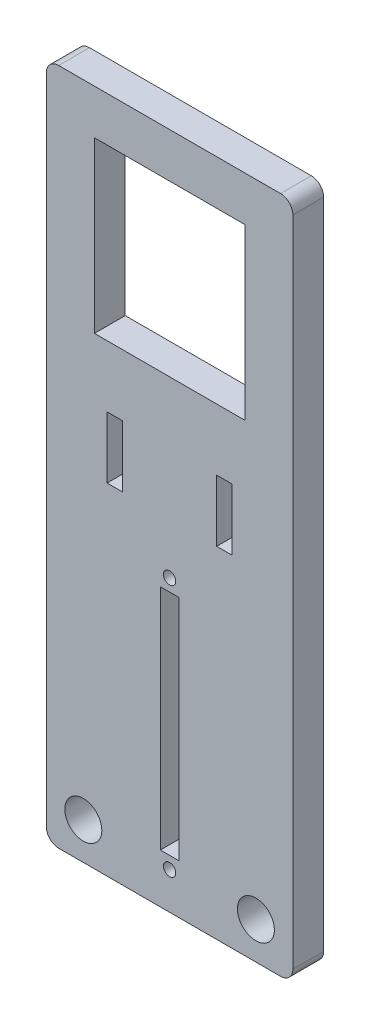
SolidWorks part; units mm, degrees
ref_plane "Front Plane" through (0, 0, 0) normal (0, 0, 1) x (1, 0, 0)
ref_plane "Top Plane" through (0, 0, 0) normal (0, 1, 0) x (1, 0, 0)
ref_plane "Right Plane" through (0, 0, 0) normal (1, 0, 0) x (0, 0, -1)
sketch "Model" plane through (0, 0, 0) normal (0, 0, 1) x (1, 0, 0)
  line L0 (0, 0) -> (0, 110)
  line L1 (0, 110) -> (40, 110)
  line L2 (40, 110) -> (40, 0)
  line L3 (40, 0) -> (0, 0)
  line L4 (18.5, 45) -> (18.5, 8)
  line L5 (18.5, 8) -> (21.5, 8)
  line L6 (21.5, 8) -> (21.5, 45)
  line L7 (21.5, 45) -> (18.5, 45)
  line L8 (7.8, 102.75) -> (7.8, 75.25)
  line L9 (7.8, 75.25) -> (32.2, 75.25)
  line L10 (32.2, 75.25) -> (32.2, 102.75)
  line L11 (32.2, 102.75) -> (7.8, 102.75)
  line L17 (9.86, 65.25) -> (12.36, 65.25)
  line L18 (9.86, 65.25) -> (9.86, 55.25)
  line L19 (9.86, 55.25) -> (12.36, 55.25)
  line L20 (12.36, 65.25) -> (12.36, 55.25)
  line L21 (27.64, 65.25) -> (30.14, 65.25)
  line L22 (27.64, 65.25) -> (27.64, 55.25)
  line L23 (27.64, 55.25) -> (30.14, 55.25)
  line L24 (30.14, 65.25) -> (30.14, 55.25)
  circle A0 centre (34, 6) radius 3
  circle A1 centre (6, 6) radius 3
  circle A2 centre (20, 6) radius 1
  circle A3 centre (20, 47) radius 1
  point P10 (20, 45)
  point P13 (20, 8)
  point P14 (0, 0)
  point P15 (11.11, 65.25)
  point P35 (0, 0)
  point P36 (28.89, 65.25)
  point P37 (0, 0)
  point P39 (0, 0)
  dimension "D7" = 6
  dimension "D9" = 6
  dimension "D10" = 6
  dimension "D11" = 6
  dimension "D13" = 41
  dimension "D14" = 2
  dimension "D15" = 2
  dimension "D16" = 2
  dimension "D17" = 20
  dimension "D1" = 40
  dimension "D2" = 110
  dimension "D3" = 7.25
  dimension "D4" = 7.8
  dimension "D5" = 24.4
  dimension "D6" = 27.5
  dimension "D8" = 6
  dimension "D12" = 37
  dimension "D18" = 3
  dimension "D19" = 10
  dimension "D20" = 2.5
  dimension "D21" = 17.78
  dimension "D22" = 9.86
  dimension "D23" = 9.86
  dimension "D24" = 10
extrude "Boss-Extrude1" add sketch "Model" along normal blind 5
fillet "Fillet1" radius 2 4 edges at (0, 0, 2.5) (40, 0, 2.5) (0, 110, 2.5) (40, 110, 2.5)
